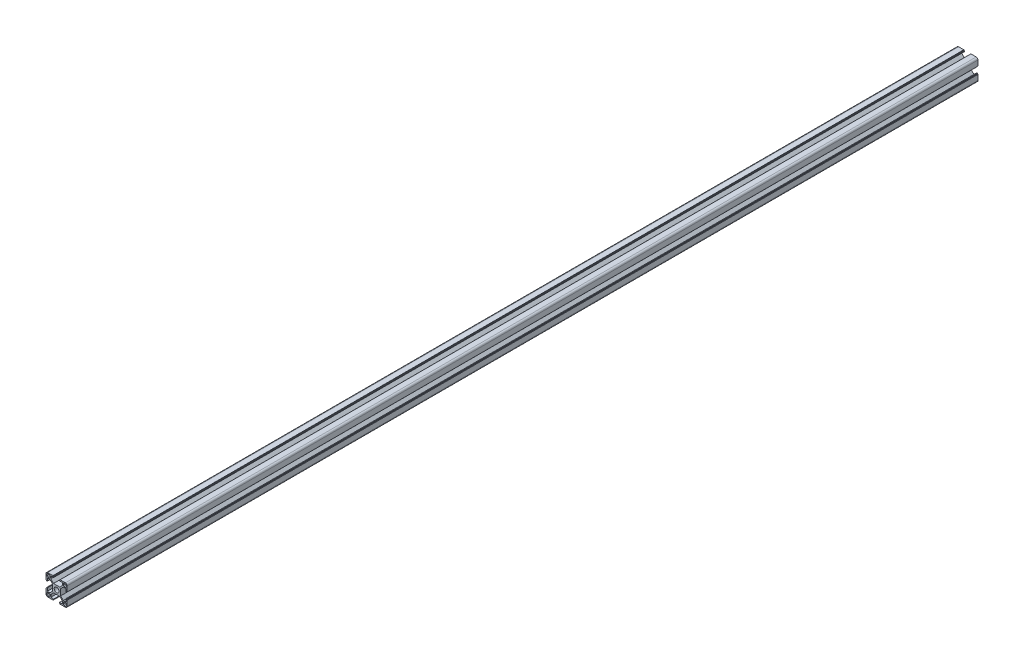
SolidWorks part; units mm, degrees
material "6061-T6 (SS)"
ref_plane "前视基准面" through (0, 0, 0) normal (0, 0, 1) x (1, 0, 0)
ref_plane "上视基准面" through (0, 0, 0) normal (0, 1, 0) x (1, 0, 0)
ref_plane "右视基准面" through (0, 0, 0) normal (1, 0, 0) x (0, 0, -1)
sketch "Sketch1" plane through (0, 0, 0) normal (0, 0, 1) x (1, 0, 0)
  line L0 (-5.1, 15) -> (-5.1, 14.2)
  line L1 (-12.5, -15) -> (12.5, -15)
  line L2 (-15, -12.5) -> (-15, 12.5)
  line L3 (-12.5, 15) -> (12.5, 15)
  line L4 (15, -12.5) -> (15, 12.5)
  line L5 (-15, -15) -> (15, 15) construction
  line L6 (-15, 15) -> (15, -15) construction
  line L7 (-5.1, 14.2) -> (-4.1, 14.2)
  line L8 (-4.1, 14.2) -> (-4.1, 13.2)
  line L9 (-4.1, 13.2) -> (-8.25, 13.2)
  line L10 (-8.25, 13.2) -> (-8.25, 9.5228)
  line L11 (-8.25, 9.5228) -> (-4.4272, 5.7)
  line L12 (-4.4272, 5.7) -> (4.4272, 5.7)
  line L13 (-5.1, 15) -> (5.1, 15)
  line L14 (0, 15) -> (0, 5.7) construction
  line L15 (8.25, 9.5228) -> (4.4272, 5.7)
  line L16 (8.25, 13.2) -> (8.25, 9.5228)
  line L17 (4.1, 13.2) -> (8.25, 13.2)
  line L18 (4.1, 14.2) -> (4.1, 13.2)
  line L19 (5.1, 14.2) -> (4.1, 14.2)
  line L20 (5.1, 15) -> (5.1, 14.2)
  line L21 (15, 5.1) -> (14.2, 5.1)
  line L22 (14.2, 5.1) -> (14.2, 4.1)
  line L23 (14.2, 4.1) -> (13.2, 4.1)
  line L24 (13.2, 4.1) -> (13.2, 8.25)
  line L25 (13.2, 8.25) -> (9.5228, 8.25)
  line L26 (9.5228, 8.25) -> (5.7, 4.4272)
  line L27 (5.7, 4.4272) -> (5.7, -4.4272)
  line L28 (15, 5.1) -> (15, -5.1)
  line L29 (9.5228, -8.25) -> (5.7, -4.4272)
  line L30 (13.2, -8.25) -> (9.5228, -8.25)
  line L31 (13.2, -4.1) -> (13.2, -8.25)
  line L32 (14.2, -4.1) -> (13.2, -4.1)
  line L33 (14.2, -5.1) -> (14.2, -4.1)
  line L34 (15, -5.1) -> (14.2, -5.1)
  line L35 (15, 0) -> (5.7, 0) construction
  line L36 (5.1, -15) -> (5.1, -14.2)
  line L37 (5.1, -14.2) -> (4.1, -14.2)
  line L38 (4.1, -14.2) -> (4.1, -13.2)
  line L39 (4.1, -13.2) -> (8.25, -13.2)
  line L40 (8.25, -13.2) -> (8.25, -9.5228)
  line L41 (8.25, -9.5228) -> (4.4272, -5.7)
  line L42 (4.4272, -5.7) -> (-4.4272, -5.7)
  line L43 (5.1, -15) -> (-5.1, -15)
  line L44 (-8.25, -9.5228) -> (-4.4272, -5.7)
  line L45 (-8.25, -13.2) -> (-8.25, -9.5228)
  line L46 (-4.1, -13.2) -> (-8.25, -13.2)
  line L47 (-4.1, -14.2) -> (-4.1, -13.2)
  line L48 (-5.1, -14.2) -> (-4.1, -14.2)
  line L49 (-5.1, -15) -> (-5.1, -14.2)
  line L50 (0, -15) -> (0, -5.7) construction
  line L51 (-15, -5.1) -> (-14.2, -5.1)
  line L52 (-14.2, -5.1) -> (-14.2, -4.1)
  line L53 (-14.2, -4.1) -> (-13.2, -4.1)
  line L54 (-13.2, -4.1) -> (-13.2, -8.25)
  line L55 (-13.2, -8.25) -> (-9.5228, -8.25)
  line L56 (-9.5228, -8.25) -> (-5.7, -4.4272)
  line L57 (-5.7, -4.4272) -> (-5.7, 4.4272)
  line L58 (-15, -5.1) -> (-15, 5.1)
  line L59 (-9.5228, 8.25) -> (-5.7, 4.4272)
  line L60 (-13.2, 8.25) -> (-9.5228, 8.25)
  line L61 (-13.2, 4.1) -> (-13.2, 8.25)
  line L62 (-14.2, 4.1) -> (-13.2, 4.1)
  line L63 (-14.2, 5.1) -> (-14.2, 4.1)
  line L64 (-15, 5.1) -> (-14.2, 5.1)
  line L65 (-15, 0) -> (-5.7, 0) construction
  line L66 (0, 0) -> (0, 5.7) construction
  circle A0 centre (0, 0) radius 3.4
  arc A1 (-12.5, -15) -> (-15, -12.5) centre (-12.5, -12.5) cw
  arc A2 (12.5, -15) -> (15, -12.5) centre (12.5, -12.5) ccw
  arc A3 (12.5, 15) -> (15, 12.5) centre (12.5, 12.5) cw
  arc A4 (-15, 12.5) -> (-12.5, 15) centre (-12.5, 12.5) cw
  point P0 (0, 0)
  dimension "D3" = 6.8
  dimension "D12" = 2.5
  dimension "D1" = 30
  dimension "D2" = 30
  dimension "D4" = 16.5
  dimension "D5" = 8.2
  dimension "D6" = 10.2
  dimension "D7" = 7.5
  dimension "D9" = 1.8
  dimension "D10" = 1.8
  dimension "D11" = 0.8
  dimension "D8" = 4
extrude "Extrude1" add sketch "Sketch1" along normal blind 1290 contours A4 L2 L64 L63 L62 L61 L60 L59 L57 L56 L55 L54 L53 L52 L51 A1 L1 L49 L48 L47 L46 L45 L44 L42 L41 L40 L39 L38 L37 L36 A2 L4 L34 L33 L32 L31 L30 L29 L27 L26 L25 L24 L23 L22 L21 A3 L3 L20
sketch "Sketch2" plane through (0, 0, 1290) normal (0, 0, 1) x (1, 0, 0)
  line L0 (13.7, 12.7) -> (13.7, 10.55)
  line L1 (-12.7, 13.7) -> (-10.55, 13.7)
  line L2 (-13.7, 12.7) -> (-13.7, 10.55)
  line L3 (-12.7, 9.55) -> (-10.55, 9.55)
  line L4 (-9.55, 12.7) -> (-9.55, 10.55)
  line L5 (-13.7, 13.7) -> (-9.55, 9.55) construction
  line L6 (-13.7, 9.55) -> (-9.55, 13.7) construction
  line L7 (12.7, 13.7) -> (10.55, 13.7)
  line L8 (9.55, 12.7) -> (9.55, 10.55)
  line L9 (12.7, 9.55) -> (10.55, 9.55)
  line L10 (12.7, -13.7) -> (10.55, -13.7)
  line L11 (13.7, -12.7) -> (13.7, -10.55)
  line L12 (12.7, -9.55) -> (10.55, -9.55)
  line L13 (9.55, -12.7) -> (9.55, -10.55)
  line L14 (-13.7, -12.7) -> (-13.7, -10.55)
  line L15 (-12.7, -13.7) -> (-10.55, -13.7)
  line L16 (-9.55, -12.7) -> (-9.55, -10.55)
  line L17 (-12.7, -9.55) -> (-10.55, -9.55)
  line L18 (0, 0) -> (-9.55, 9.55) construction
  line L19 (-12.5, 15) -> (-5.1, 15) construction
  line L20 (-15, 5.1) -> (-15, 12.5) construction
  line L21 (-13.2, 8.25) -> (-9.5228, 8.25) construction
  line L22 (-8.25, 13.2) -> (-8.25, 9.5228) construction
  arc A0 (-13.7, -12.7) -> (-12.7, -13.7) centre (-12.7, -12.7) ccw
  arc A1 (-10.55, -13.7) -> (-9.55, -12.7) centre (-10.55, -12.7) ccw
  arc A2 (-9.55, -10.55) -> (-10.55, -9.55) centre (-10.55, -10.55) ccw
  arc A3 (-13.7, -10.55) -> (-12.7, -9.55) centre (-12.7, -10.55) cw
  arc A4 (13.7, -10.55) -> (12.7, -9.55) centre (12.7, -10.55) ccw
  arc A5 (12.7, -13.7) -> (13.7, -12.7) centre (12.7, -12.7) ccw
  arc A6 (10.55, -13.7) -> (9.55, -12.7) centre (10.55, -12.7) cw
  arc A7 (10.55, -9.55) -> (9.55, -10.55) centre (10.55, -10.55) ccw
  arc A8 (13.7, 12.7) -> (12.7, 13.7) centre (12.7, 12.7) ccw
  arc A9 (13.7, 10.55) -> (12.7, 9.55) centre (12.7, 10.55) cw
  arc A10 (9.55, 10.55) -> (10.55, 9.55) centre (10.55, 10.55) ccw
  arc A11 (10.55, 13.7) -> (9.55, 12.7) centre (10.55, 12.7) ccw
  arc A12 (-10.55, 13.7) -> (-9.55, 12.7) centre (-10.55, 12.7) cw
  arc A13 (-10.55, 9.55) -> (-9.55, 10.55) centre (-10.55, 10.55) ccw
  arc A14 (-13.7, 10.55) -> (-12.7, 9.55) centre (-12.7, 10.55) ccw
  arc A15 (-12.7, 13.7) -> (-13.7, 12.7) centre (-12.7, 12.7) ccw
  point P0 (-11.625, 11.625)
  dimension "D2" = 1
  dimension "D3" = 1.3
  dimension "D4" = 1.3
  dimension "D5" = 1.3
  dimension "D6" = 1.3
  dimension "D1" = 4
extrude "Extrude2" cut sketch "Sketch2" against normal through all
